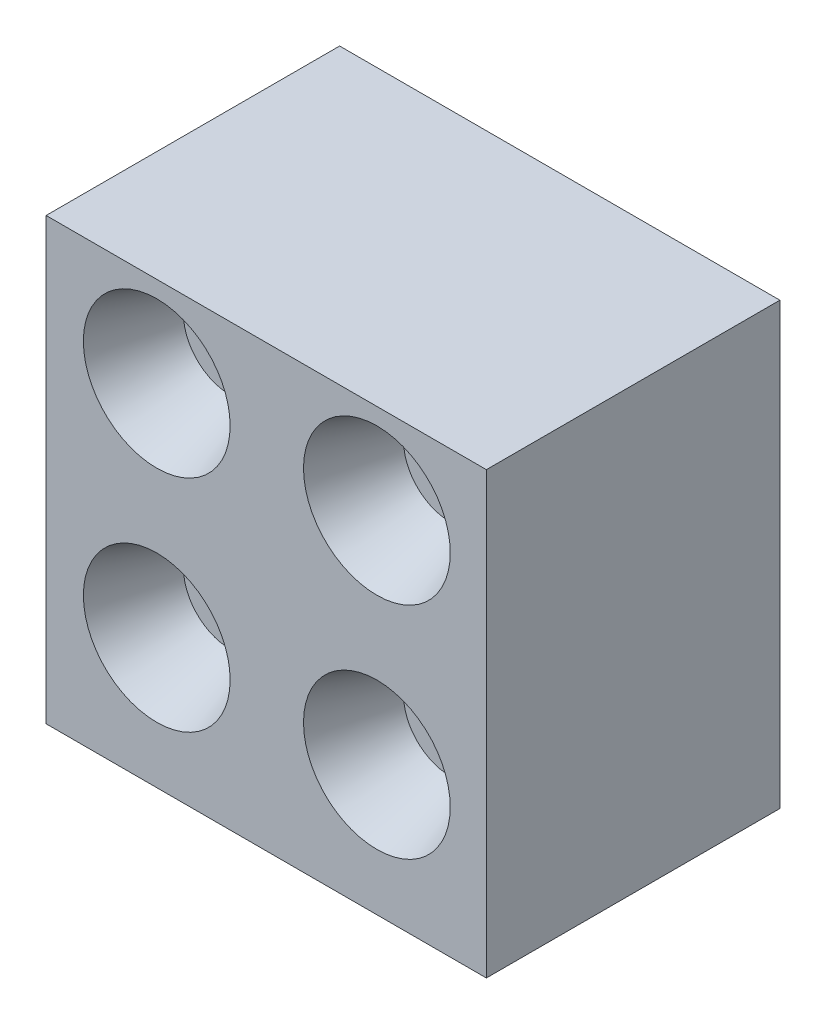
SolidWorks part; units mm, degrees
ref_plane "Front Plane" through (0, 0, 0) normal (0, 0, 1) x (1, 0, 0)
ref_plane "Top Plane" through (0, 0, 0) normal (0, 1, 0) x (1, 0, 0)
ref_plane "Right Plane" through (0, 0, 0) normal (1, 0, 0) x (0, 0, -1)
sketch "Sketch1" plane through (0, 0, 0) normal (0, 0, 1) x (1, 0, 0)
  line L1 (0, 0) -> (3048, 0)
  line L2 (0, 0) -> (0, 3048)
  line L3 (0, 3048) -> (3048, 3048)
  line L4 (3048, 0) -> (3048, 3048)
extrude "Boss-Extrude1" add sketch "Sketch1" along normal blind 2032
sketch "Sketch2" plane through (0, 0, 0) normal (0, 0, 1) x (1, 0, 0)
  circle A0 centre (765.9284, 2423.7315) radius 508
  dimension "D1" = 1016
extrude "Cut-Extrude1" cut sketch "Sketch2" against normal blind 508 draft 20 from surface at 2032 starting at face at (1524, 1524, 2032)
pattern_linear "LPattern1" count 2 spacing 1524 along (1, 0, 0) count 2 spacing 1524 along (0, -1, 0) of "Cut-Extrude1"
